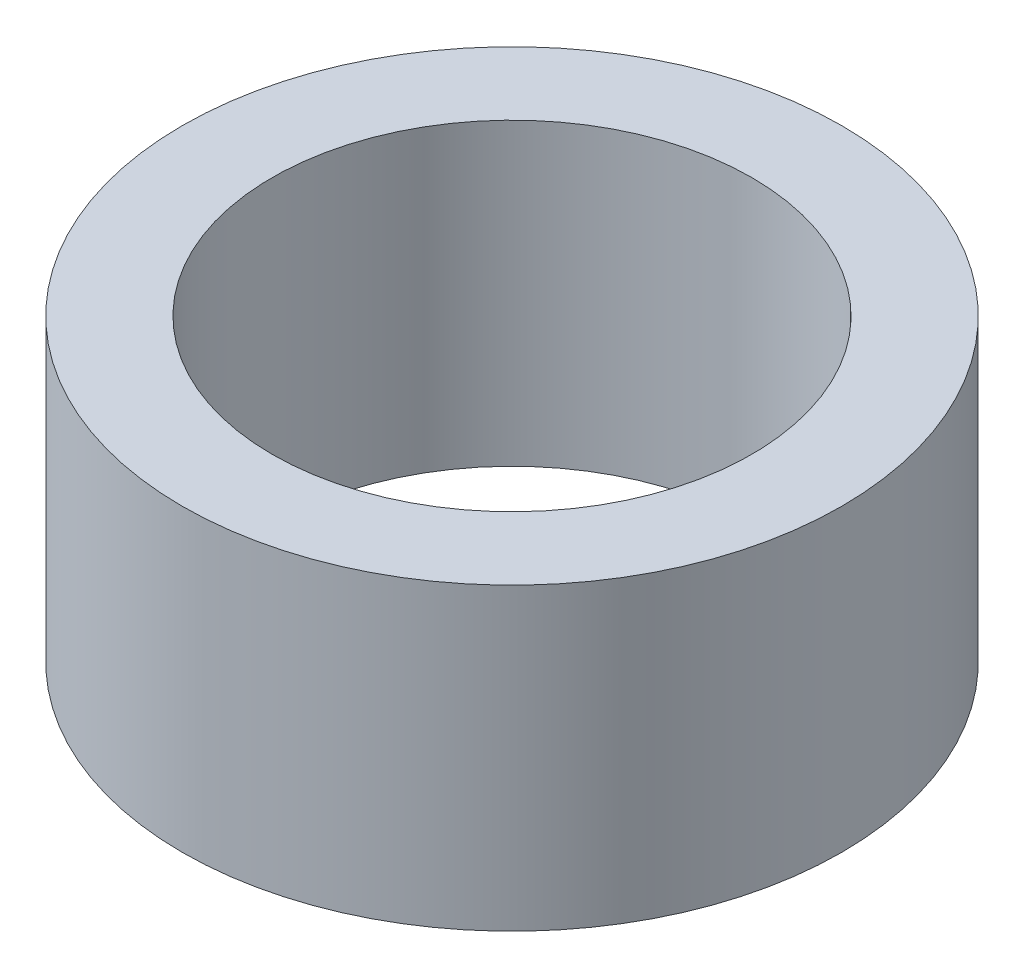
SolidWorks part; units mm, degrees
ref_plane "Plan de face" through (0, 0, 0) normal (0, 0, 1) x (1, 0, 0)
ref_plane "Plan de dessus" through (0, 0, 0) normal (0, 1, 0) x (1, 0, 0)
ref_plane "Plan de droite" through (0, 0, 0) normal (1, 0, 0) x (0, 0, -1)
sketch "Esquisse1" plane through (0, 0, 0) normal (0, 1, 0) x (1, 0, 0)
  circle A0 centre (0, 0) radius 2.2
  circle A1 centre (0, 0) radius 1.6
  dimension "D1" = 3.2
  dimension "D2" = 0.6
extrude "Boss.-Extru.1" add sketch "Esquisse1" along normal blind 2
